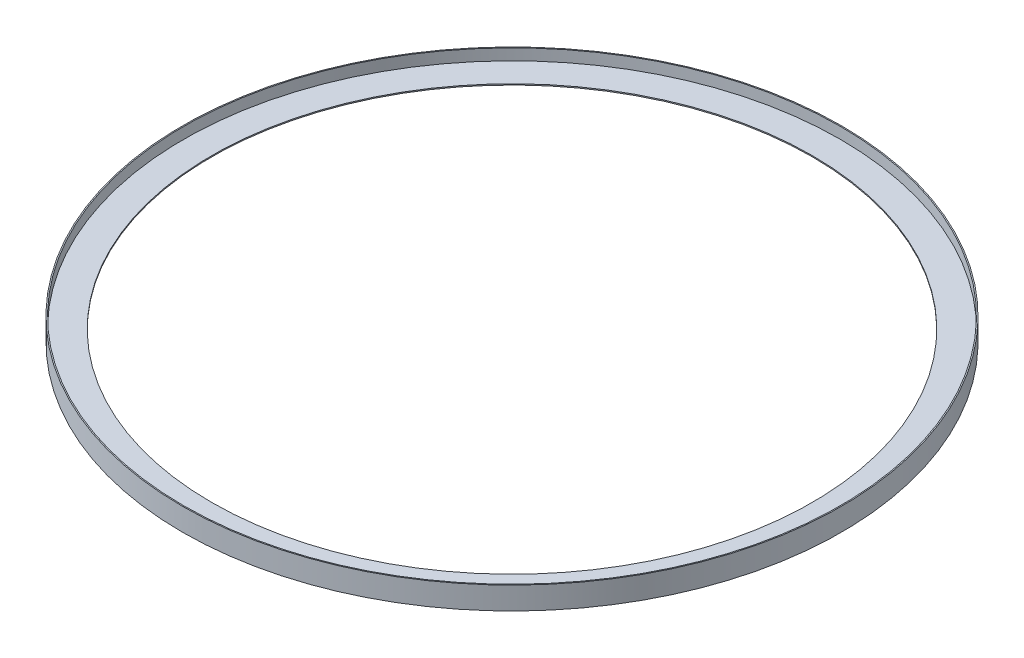
SolidWorks part; units mm, degrees
ref_plane "前视基准面" through (0, 0, 0) normal (0, 0, 1) x (1, 0, 0)
ref_plane "上视基准面" through (0, 0, 0) normal (0, 1, 0) x (1, 0, 0)
ref_plane "右视基准面" through (0, 0, 0) normal (1, 0, 0) x (0, 0, -1)
other "Configuration Table"
sketch "草图1" plane through (0, 0, 0) normal (0, 1, 0) x (1, 0, 0)
  circle A0 centre (0, 0) radius 292.5
  circle A1 centre (0, 0) radius 267.5
  dimension "D1" = 585
  dimension "D2" = 535
extrude "凸台-拉伸1" add sketch "草图1" along normal mid plane 1
sketch "草图2" plane through (0, 0.5, 0) normal (0, 1, 0) x (1, 0, 0)
  circle A0 centre (0, 0) radius 292.5
  circle A1 centre (0, 0) radius 293.5
  dimension "D1" = 1
  dimension "D2" = 585
extrude "凸台-拉伸2" add sketch "草图2" along normal mid plane 20
